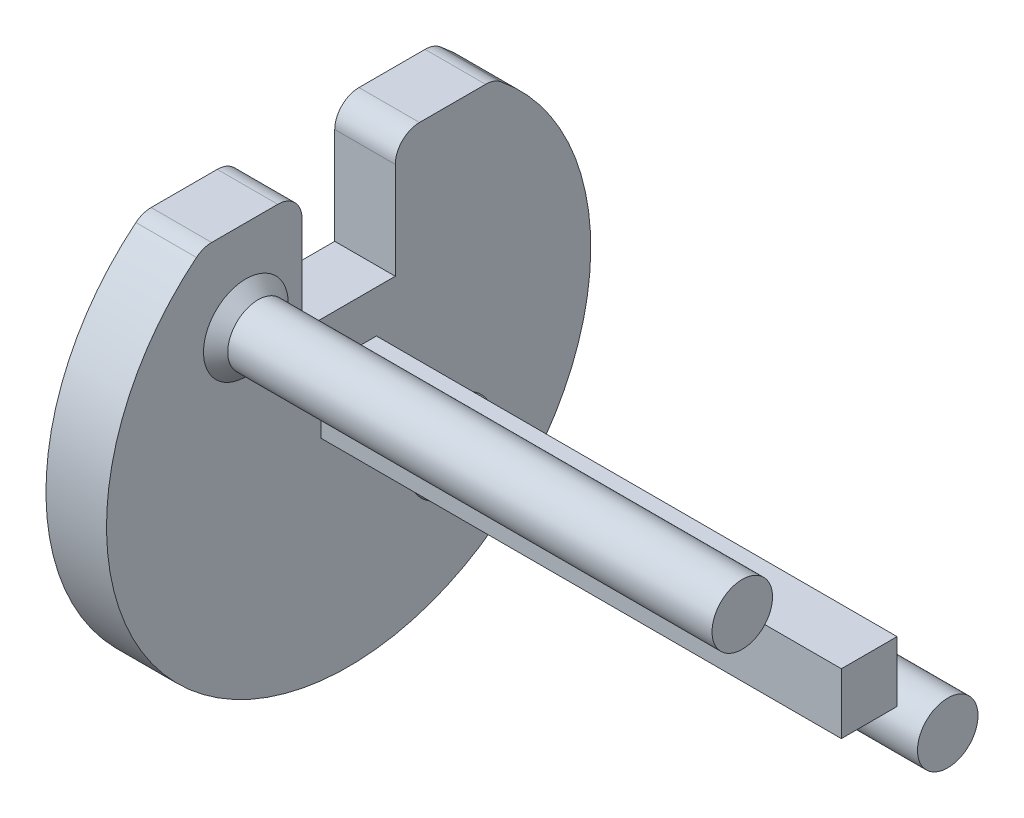
SolidWorks part; units mm, degrees
ref_plane "Front Plane" through (0, 0, 0) normal (0, 0, 1) x (1, 0, 0)
ref_plane "Top Plane" through (0, 0, 0) normal (0, 1, 0) x (1, 0, 0)
ref_plane "Right Plane" through (0, 0, 0) normal (1, 0, 0) x (0, 0, -1)
sketch "Sketch2" plane through (0, 0, 0) normal (1, 0, 0) x (0, 0, -1)
  circle A0 centre (0, 0) radius 20
  dimension "D1" = 40
extrude "Boss-Extrude2" add sketch "Sketch2" along normal blind 5
sketch "Sketch3" plane through (5, 0, 0) normal (1, 0, 0) x (0, 0, -1)
  line L1 (-2.5, -2.5) -> (2.5, -2.5)
  line L2 (-2.5, -2.5) -> (-2.5, 2.5)
  line L3 (-2.5, 2.5) -> (2.5, 2.5)
  line L4 (2.5, -2.5) -> (2.5, 2.5)
  line L5 (-2.5, -2.5) -> (2.5, 2.5) construction
  line L6 (-2.5, 2.5) -> (2.5, -2.5) construction
  point P0 (0, 0)
  dimension "D1" = 5
  dimension "D2" = 5
extrude "Boss-Extrude3" add sketch "Sketch3" along normal blind 43
sketch "Sketch4" plane through (5, 0, 0) normal (1, 0, 0) x (0, 0, -1)
  line L0 (8.4853, -8.4853) -> (-8.4853, 8.4853)
  line L1 (0, 0) -> (0, 50000) construction
  circle A1 centre (-8.4853, 8.4853) radius 2.5
  circle A2 centre (8.4853, -8.4853) radius 2.5
  point P4 (0, 0)
  dimension "D3" = 5
  dimension "D4" = 5
  dimension "D1" = 45
  dimension "D2" = 12
extrude "Boss-Extrude4" add sketch "Sketch4" along normal blind 41
sketch "Sketch5" plane through (5, 0, 0) normal (1, 0, 0) x (0, 0, -1)
  line L0 (2.5, 2.5) -> (-2.5, 2.5) construction
  line L1 (-3.8523, 6) -> (3.8523, 6)
  line L2 (-3.8523, 6) -> (-3.8523, 20)
  line L3 (-3.8523, 20) -> (3.8523, 20)
  line L4 (3.8523, 6) -> (3.8523, 20)
  line L6 (-20, 20) -> (20, 20)
  line L7 (-20, 20) -> (-20, 16)
  line L8 (-20, 16) -> (20, 16)
  line L9 (20, 20) -> (20, 16)
  circle A0 centre (0, 0) radius 20 construction
  point P6 (0, 2.5)
  point P7 (0, 6)
  circle M7 centre (0, 0) radius 20
  dimension "D1" = 14
  dimension "D2" = 4
extrude "Cut-Extrude1" cut sketch "Sketch5" against normal through all contours L8 L2 M7 | L2 L8 L4 M7 | L4 L8 M7 | L8 L2 L1 L4
fillet "Fillet1" radius 2 4 edges at (2.5, 16, -12) (2.5, 16, 12) (2.5, 16, -3.8523) (2.5, 16, 3.8523)
chamfer "Chamfer1" distance 1 angle 45 2 edges at (5, -8.4853, -10.9853) (5, 8.4853, 5.9853)
sketch "Sketch6" plane through (0, 0, -2.5) normal (0, 0, -1) x (-1, 0, 0)
  line L4 (-5, -2.5) -> (-5, 2.5)
  line L5 (-5, 2.5) -> (-48, 2.5)
  line L6 (-48, 2.5) -> (-48, -2.5)
  line L7 (-48, -2.5) -> (-5, -2.5)
  line L8 (-5, -2.5) -> (-5, 2.5)
  line L9 (-5, 2.5) -> (-48, 2.5)
  line L10 (-48, 2.5) -> (-48, -2.5)
  line L11 (-48, -2.5) -> (-5, -2.5)
  dimension "D1" = 0
extrude "Cut-Extrude2" cut sketch "Sketch6" against normal blind 0.2
sketch "Sketch7" plane through (0, 0, 2.5) normal (0, 0, 1) x (1, 0, 0)
  line L4 (5, 2.5) -> (5, -2.5)
  line L5 (5, -2.5) -> (48, -2.5)
  line L6 (48, -2.5) -> (48, 2.5)
  line L7 (48, 2.5) -> (5, 2.5)
  line L8 (5, 2.5) -> (5, -2.5)
  line L9 (5, -2.5) -> (48, -2.5)
  line L10 (48, -2.5) -> (48, 2.5)
  line L11 (48, 2.5) -> (5, 2.5)
  dimension "D1" = 0
extrude "Cut-Extrude3" cut sketch "Sketch7" against normal blind 0.2
